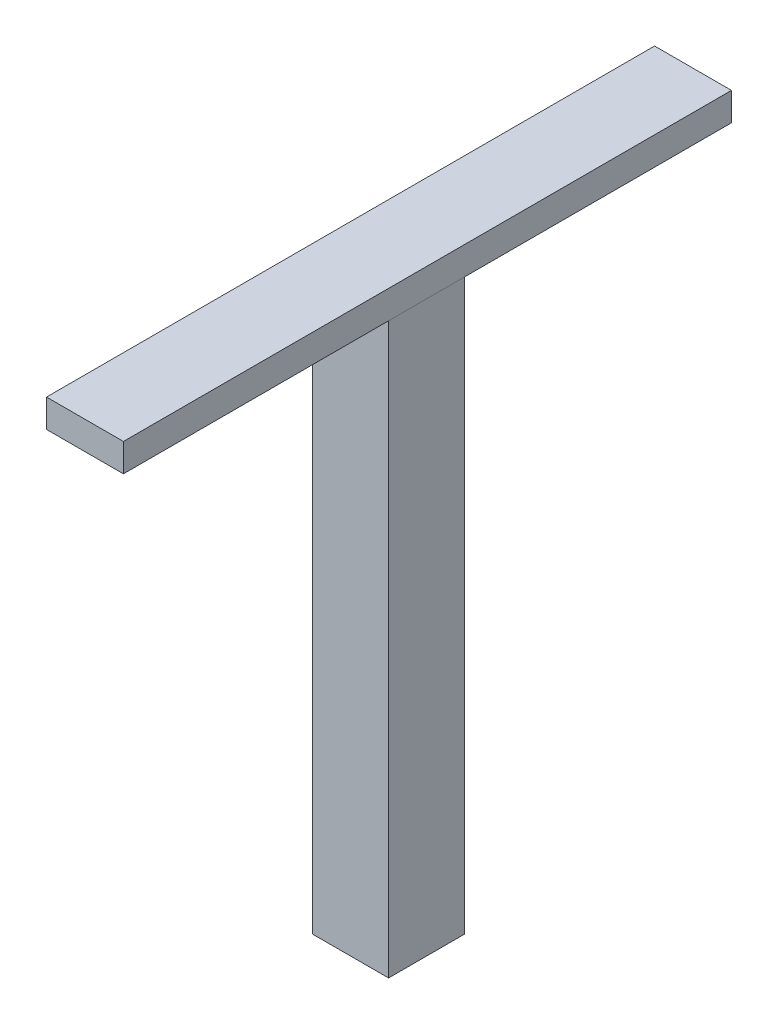
SolidWorks part; units mm, degrees
material "普通碳钢"
ref_plane "前视基准面" through (0, 0, 0) normal (0, 0, 1) x (1, 0, 0)
ref_plane "上视基准面" through (0, 0, 0) normal (0, 1, 0) x (1, 0, 0)
ref_plane "右视基准面" through (0, 0, 0) normal (1, 0, 0) x (0, 0, -1)
other "Configuration Table"
sketch3d "3D草图1"
  line L5 (0, 0, 0) -> (20, 0, 0)
  line L6 (0, 0, 0) -> (0, 0, 20)
  line L7 (0, 0, 20) -> (20, 0, 20)
  line L8 (20, 0, 0) -> (20, 0, 20)
  dimension "D1" = 20
  dimension "D2" = 20
extrude "凸台-拉伸1" add sketch "3D草图1" along direction (0, 1, 0) on the side of the normal blind 150 contours L6 L5 L8 L7
sketch "草图7" plane through (0, 0, 20) normal (0, 0, 1) x (1, 0, 0)
  line L1 (0, 150) -> (20.2325, 150)
  line L2 (0, 150) -> (0, 157.3892)
  line L3 (0, 157.3892) -> (20.2325, 157.3892)
  line L4 (20.2325, 150) -> (20.2325, 157.3892)
extrude "凸台-拉伸2" add sketch "草图7" along normal blind 70 and the other way blind 90 separate body
